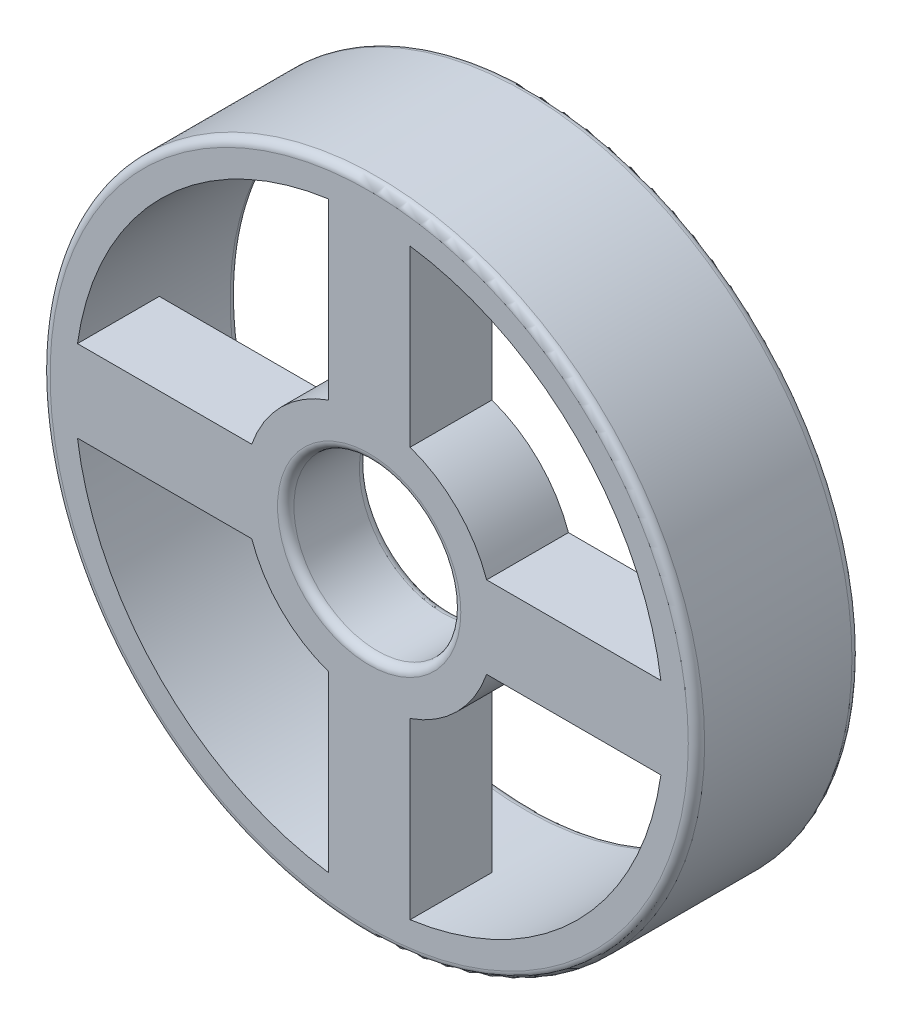
SolidWorks part; units mm, degrees
ref_plane "Front Plane" through (0, 0, 0) normal (0, 0, 1) x (1, 0, 0)
ref_plane "Top Plane" through (0, 0, 0) normal (0, 1, 0) x (1, 0, 0)
ref_plane "Right Plane" through (0, 0, 0) normal (1, 0, 0) x (0, 0, -1)
sketch "Sketch2" plane through (0, 0, 0) normal (0, 0, 1) x (1, 0, 0)
  circle A0 centre (0, 0) radius 20
  dimension "D1" = 40
extrude "Boss-Extrude1" add sketch "Sketch2" along normal blind 10
sketch "Sketch4" plane through (0, 0, 10) normal (0, 0, 1) x (1, 0, 0)
  line L0 (-2.5, 17.8255) -> (-2.5, 7.177)
  line L1 (2.5, 17.8255) -> (2.5, 7.177)
  line L2 (-2.5, 7.177) -> (2.5, 7.177) construction
  line L3 (7.177, 2.5) -> (17.8255, 2.5)
  line L4 (7.177, -2.5) -> (17.8255, -2.5)
  line L5 (-7.177, 2.5) -> (-17.8255, 2.5)
  line L6 (-7.177, -2.5) -> (-17.8255, -2.5)
  line L7 (-2.5, -7.177) -> (-2.5, -17.8255)
  line L8 (2.5, -7.177) -> (2.5, -17.8255)
  circle A0 centre (0, 0) radius 5.1
  circle A1 centre (0, 0) radius 20 construction
  circle A2 centre (0, 0) radius 20 construction
  circle A3 centre (0, 0) radius 18 construction
  circle A4 centre (0, 0) radius 7.6 construction
  arc A6 (2.5, 7.177) -> (7.177, 2.5) centre (0, 0) cw
  arc A7 (-7.177, 2.5) -> (-2.5, 7.177) centre (0, 0) cw
  arc A8 (-2.5, -7.177) -> (-7.177, -2.5) centre (0, 0) cw
  arc A9 (2.5, -7.177) -> (7.177, -2.5) centre (0, 0) ccw
  arc A10 (2.5, 17.8255) -> (17.8255, 2.5) centre (0, 0) cw
  arc A11 (-17.8255, 2.5) -> (-2.5, 17.8255) centre (0, 0) cw
  arc A12 (-2.5, -17.8255) -> (-17.8255, -2.5) centre (0, 0) cw
  arc A13 (2.5, -17.8255) -> (17.8255, -2.5) centre (0, 0) ccw
  point P11 (0, 7.177)
  dimension "D1" = 10.2
  dimension "D2" = 2
  dimension "D4" = 2.5
  dimension "D3" = 5
extrude "Cut-Extrude1" cut sketch "Sketch4" against normal through all
sketch "Sketch5" plane through (0, 0, 0) normal (0, 0, -1) x (-1, 0, 0)
  arc A0 (-2.5, 17.8255) -> (-17.8255, 2.5) centre (0, 0) ccw construction
  arc A1 (-2.5, 17.8255) -> (-17.8255, 2.5) centre (0, 0) ccw construction
  circle A2 centre (0, 0) radius 18
extrude "Cut-Extrude2" cut sketch "Sketch5" against normal blind 5
fillet "Fillet1" radius 0.5 5 edges at (-5.1, 0, 5) (5.1, 0, 10) (-18, 0, 0) (20, 0, 0) (20, 0, 10)
